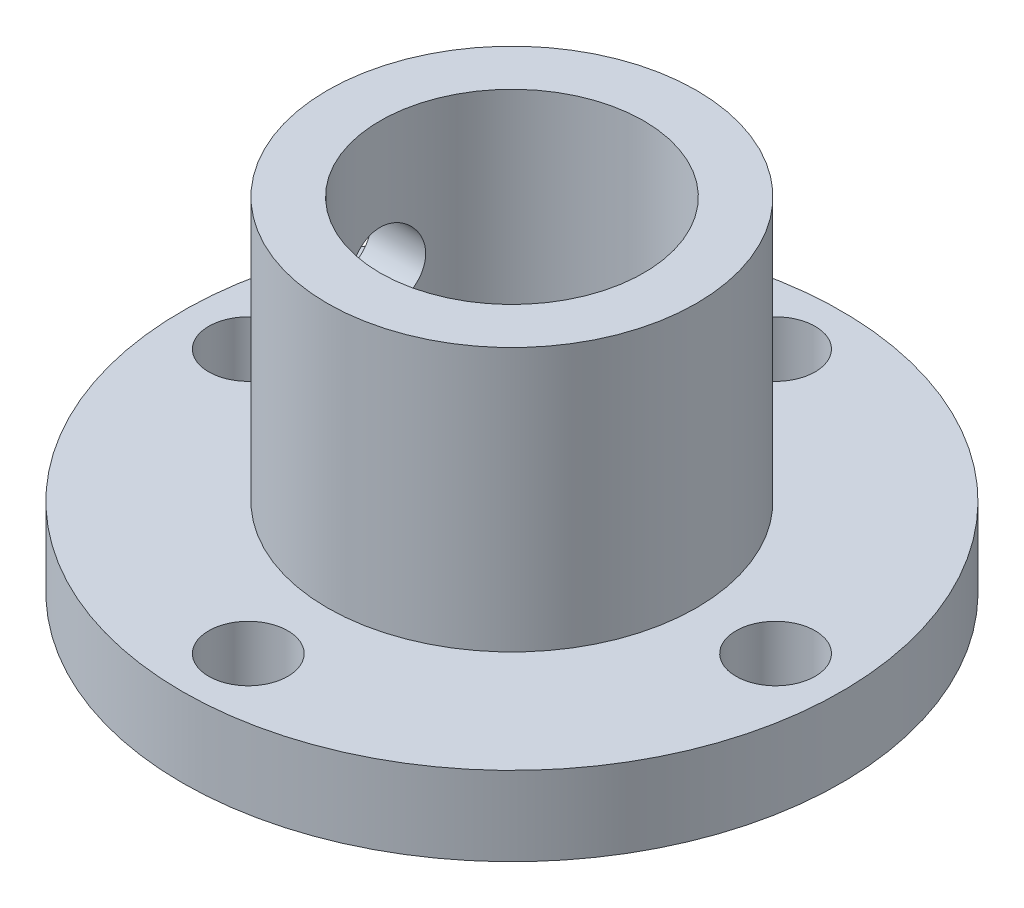
SolidWorks part; units mm, degrees
ref_plane "Ön Düzlem" through (0, 0, 0) normal (0, 0, 1) x (1, 0, 0)
ref_plane "Üst Düzlem" through (0, 0, 0) normal (0, 1, 0) x (1, 0, 0)
ref_plane "Sağ Düzlem" through (0, 0, 0) normal (1, 0, 0) x (0, 0, -1)
sketch "Çizim1" plane through (0, 0, 0) normal (0, 1, 0) x (1, 0, 0)
  circle A0 centre (0, 0) radius 12.5
  circle A1 centre (0, 0) radius 10 construction
  circle A2 centre (10, 0) radius 1.5
  circle A3 centre (0, -10) radius 1.5
  circle A4 centre (-10, 0) radius 1.5
  circle A5 centre (0, 10) radius 1.5
  point P15 (0, 0)
  dimension "D2" = 3
  dimension "D3" = 25
  dimension "D4" = 20
  dimension "D1" = 4
extrude "Yükseklik-Ekstrüzyon1" add sketch "Çizim1" along normal blind 3
sketch "Çizim2" plane through (0, 3, 0) normal (0, 1, 0) x (1, 0, 0)
  circle A0 centre (0, 0) radius 5
  dimension "D1" = 10
extrude "Ekstrüzyon-İnce1" add sketch "Çizim2" along normal blind 10 thin
sketch "Çizim3" plane through (0, 0, 0) normal (1, 0, 0) x (0, 0, -1)
  line L0 (0, 13) -> (0, 3) construction
  line L1 (7, 13) -> (-7, 13) construction
  line L2 (12.5, 3) -> (-12.5, 3) construction
  circle A0 centre (0, 8) radius 1.5
  dimension "D1" = 3
extrude "Kes-Ekstrüzyon1" cut sketch "Çizim3" against normal through all
